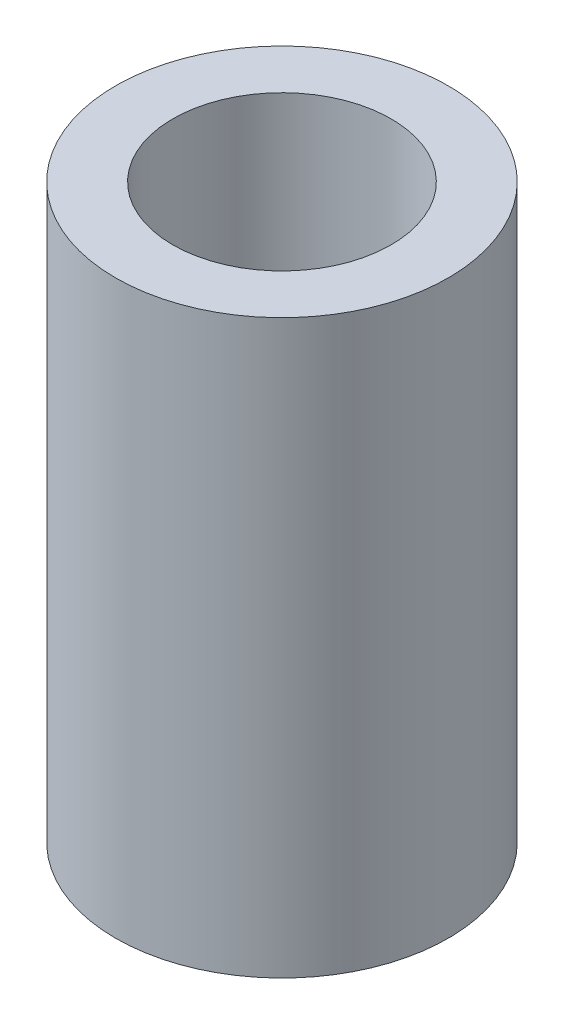
SolidWorks part; units mm, degrees
ref_plane "Front Plane" through (0, 0, 0) normal (0, 0, 1) x (1, 0, 0)
ref_plane "Top Plane" through (0, 0, 0) normal (0, 1, 0) x (1, 0, 0)
ref_plane "Right Plane" through (0, 0, 0) normal (1, 0, 0) x (0, 0, -1)
sketch "Sketch1" plane through (0, 0, 0) normal (0, 1, 0) x (1, 0, 0)
  circle A0 centre (0, 0) radius 2.667
  circle A1 centre (0, 0) radius 4.064
  dimension "D1" = 5.334
  dimension "D2" = 8.128
extrude "Boss-Extrude1" add sketch "Sketch1" along normal blind 13.97
